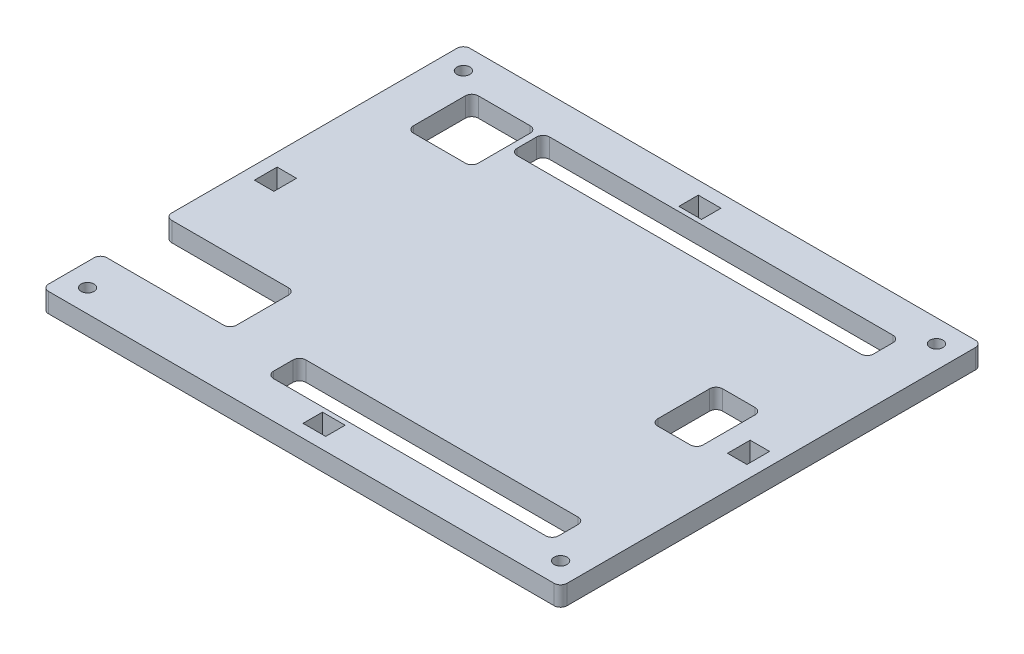
SolidWorks part; units mm, degrees
ref_plane "Alzado" through (0, 0, 0) normal (0, 0, 1) x (1, 0, 0)
ref_plane "Planta" through (0, 0, 0) normal (0, 1, 0) x (1, 0, 0)
ref_plane "Vista lateral" through (0, 0, 0) normal (1, 0, 0) x (0, 0, -1)
sketch "Croquis1" plane through (0, 0, 0) normal (0, 1, 0) x (1, 0, 0)
  line L0 (0, 69.9395) -> (0, -51.4016) construction
  line L1 (-39, -32.5) -> (39, -32.5)
  line L2 (-40, -31.5) -> (-40, -24.5)
  line L3 (-39, 32.5) -> (39, 32.5)
  line L4 (40, -31.5) -> (40, 31.5)
  line L5 (-40, -32.5) -> (40, 32.5) construction
  line L6 (-40, 32.5) -> (40, -32.5) construction
  line L7 (-63.6357, 0) -> (66.5605, 0) construction
  line L8 (-38, -1.75) -> (-35, -1.75)
  line L9 (-38, -1.75) -> (-38, 1.75)
  line L10 (-38, 1.75) -> (-35, 1.75)
  line L11 (-35, -1.75) -> (-35, 1.75)
  line L12 (-38, -1.75) -> (-35, 1.75) construction
  line L13 (-38, 1.75) -> (-35, -1.75) construction
  line L14 (38, -1.75) -> (35, -1.75)
  line L15 (38, 1.75) -> (35, -1.75) construction
  line L16 (38, -1.75) -> (35, 1.75) construction
  line L17 (35, -1.75) -> (35, 1.75)
  line L18 (38, 1.75) -> (35, 1.75)
  line L19 (38, -1.75) -> (38, 1.75)
  line L20 (-1.75, 27.5) -> (1.75, 30.5) construction
  line L21 (-1.75, -30.5) -> (1.75, -30.5)
  line L22 (-1.75, -30.5) -> (-1.75, -27.5)
  line L23 (-1.75, -27.5) -> (1.75, -27.5)
  line L24 (1.75, -30.5) -> (1.75, -27.5)
  line L25 (-1.75, -30.5) -> (1.75, -27.5) construction
  line L26 (-1.75, -27.5) -> (1.75, -30.5) construction
  line L27 (-1.75, 30.5) -> (1.75, 27.5) construction
  line L28 (1.75, 30.5) -> (1.75, 27.5)
  line L29 (-1.75, 27.5) -> (1.75, 27.5)
  line L30 (-1.75, 30.5) -> (-1.75, 27.5)
  line L31 (-1.75, 30.5) -> (1.75, 30.5)
  line L32 (-40, -12.5) -> (-40, 31.5)
  line L33 (-10, -26.8) -> (32, -26.8)
  line L34 (-11, -25.8) -> (-11, -22.8)
  line L35 (-10, -21.8) -> (32, -21.8)
  line L36 (33, -25.8) -> (33, -22.8)
  line L37 (26, 6.5) -> (31, 6.5)
  line L38 (25, 5.5) -> (25, -2.5)
  line L39 (26, -3.5) -> (31, -3.5)
  line L40 (32, 5.5) -> (32, -2.5)
  line L41 (-21, 26.8) -> (32, 26.8)
  line L42 (-22, 25.8) -> (-22, 22.8)
  line L43 (-21, 21.8) -> (32, 21.8)
  line L44 (33, 25.8) -> (33, 22.8)
  line L45 (-39, -13.5) -> (-21, -13.5)
  line L47 (-39, -23.5) -> (-21, -23.5)
  line L48 (-20, -14.5) -> (-20, -22.5)
  line L49 (-32, 26.8) -> (-24, 26.8)
  line L50 (-33, 25.8) -> (-33, 17.8)
  line L51 (-32, 16.8) -> (-24, 16.8)
  line L52 (-23, 25.8) -> (-23, 17.8)
  circle A0 centre (-36.5, 29) radius 1
  circle A1 centre (-36.5, -29) radius 1
  circle A2 centre (36.5, 29) radius 1
  circle A3 centre (36.5, -29) radius 1
  arc A4 (32, -21.8) -> (33, -22.8) centre (32, -22.8) cw
  arc A5 (32, -26.8) -> (33, -25.8) centre (32, -25.8) ccw
  arc A6 (-11, -25.8) -> (-10, -26.8) centre (-10, -25.8) ccw
  arc A7 (-11, -22.8) -> (-10, -21.8) centre (-10, -22.8) cw
  arc A8 (39, -32.5) -> (40, -31.5) centre (39, -31.5) ccw
  arc A9 (-39, -32.5) -> (-40, -31.5) centre (-39, -31.5) cw
  arc A10 (-40, -24.5) -> (-39, -23.5) centre (-39, -24.5) cw
  arc A11 (-21, -23.5) -> (-20, -22.5) centre (-21, -22.5) ccw
  arc A12 (25, -2.5) -> (26, -3.5) centre (26, -2.5) ccw
  arc A13 (31, -3.5) -> (32, -2.5) centre (31, -2.5) ccw
  arc A14 (31, 6.5) -> (32, 5.5) centre (31, 5.5) cw
  arc A15 (26, 6.5) -> (25, 5.5) centre (26, 5.5) ccw
  arc A16 (-21, -13.5) -> (-20, -14.5) centre (-21, -14.5) cw
  arc A17 (-39, -13.5) -> (-40, -12.5) centre (-39, -12.5) cw
  arc A18 (-33, 17.8) -> (-32, 16.8) centre (-32, 17.8) ccw
  arc A19 (-24, 16.8) -> (-23, 17.8) centre (-24, 17.8) ccw
  arc A20 (-22, 22.8) -> (-21, 21.8) centre (-21, 22.8) ccw
  arc A21 (32, 21.8) -> (33, 22.8) centre (32, 22.8) ccw
  arc A22 (-32, 26.8) -> (-33, 25.8) centre (-32, 25.8) ccw
  arc A23 (-24, 26.8) -> (-23, 25.8) centre (-24, 25.8) cw
  arc A24 (-21, 26.8) -> (-22, 25.8) centre (-21, 25.8) ccw
  arc A25 (32, 26.8) -> (33, 25.8) centre (32, 25.8) cw
  arc A26 (39, 32.5) -> (40, 31.5) centre (39, 31.5) cw
  arc A27 (-40, 31.5) -> (-39, 32.5) centre (-39, 31.5) cw
  point P0 (0, 0)
  point P15 (-36.5, 0)
  point P27 (36.5, 0)
  point P28 (0, -29)
  point P38 (0, 29)
  point P44 (33, -21.8)
  point P47 (33, -26.8)
  point P52 (-11, -21.8)
  point P77 (-40, -23.5)
  point P80 (-20, -23.5)
  point P83 (25, -3.5)
  point P86 (32, -3.5)
  point P89 (32, 6.5)
  point P94 (-20, -13.5)
  point P97 (-40, -13.5)
  point P100 (-33, 16.8)
  point P105 (-22, 21.8)
  point P108 (33, 21.8)
  point P111 (-33, 26.8)
  point P114 (-23, 26.8)
  point P119 (33, 26.8)
  dimension "D3" = 2
  dimension "D6" = 3.5
  dimension "D9" = 3.5
  dimension "D10" = 3.5
  dimension "D19" = 1
  dimension "D34" = 1
  dimension "D1" = 80
  dimension "D2" = 65
  dimension "D4" = 3.5
  dimension "D5" = 3.5
  dimension "D7" = 3.5
  dimension "D11" = 3.5
  dimension "D12" = 3
  dimension "D13" = 3.5
  dimension "D14" = 3
  dimension "D15" = 5.7
  dimension "D16" = 5
  dimension "D17" = 44
  dimension "D18" = 7
  dimension "D20" = 10
  dimension "D21" = 7
  dimension "D22" = 26
  dimension "D23" = 8
  dimension "D24" = 55
  dimension "D25" = 5
  dimension "D26" = 5.7
  dimension "D27" = 7
  dimension "D28" = 20
  dimension "D29" = 10
  dimension "D30" = 9
  dimension "D31" = 10
  dimension "D32" = 10
  dimension "D33" = 7
  dimension "D8" = 2
extrude "Saliente-Extruir1" add sketch "Croquis1" along normal blind 3
